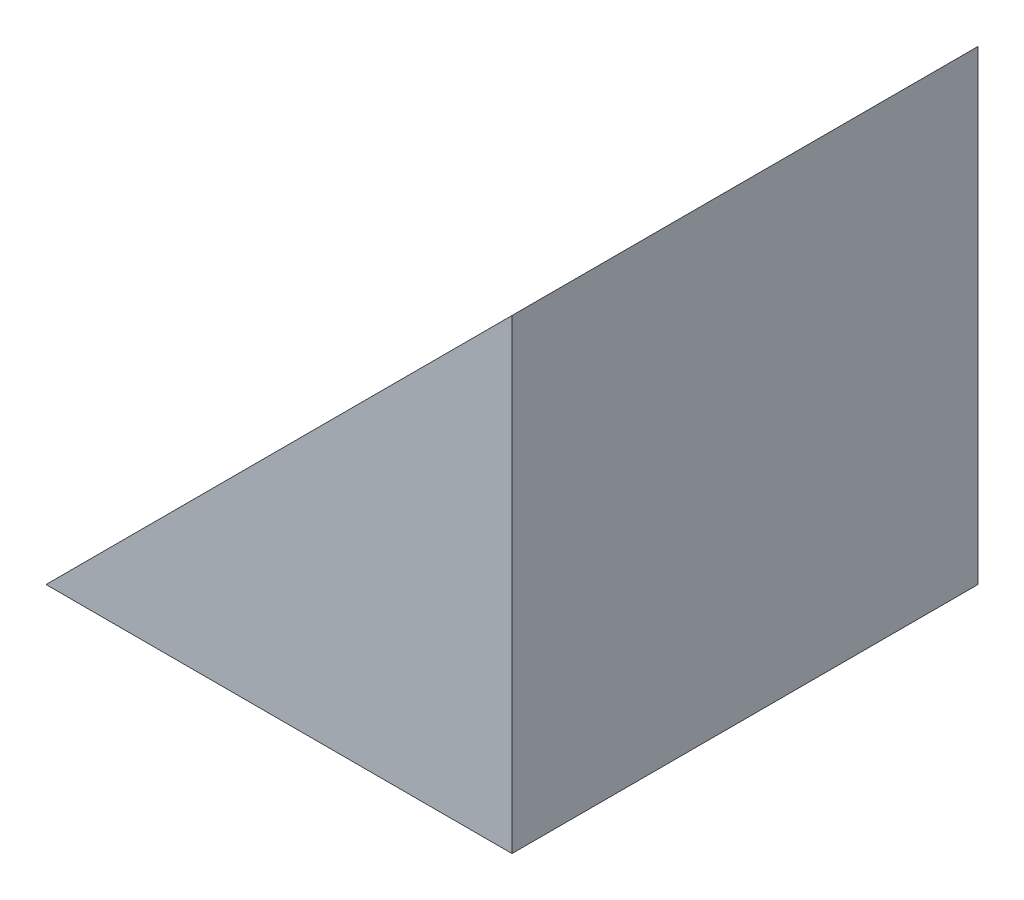
SolidWorks part; units mm, degrees
material "Glass"
ref_plane "Front Plane" through (0, 0, 0) normal (0, 0, 1) x (1, 0, 0)
ref_plane "Top Plane" through (0, 0, 0) normal (0, 1, 0) x (1, 0, 0)
ref_plane "Right Plane" through (0, 0, 0) normal (1, 0, 0) x (0, 0, -1)
sketch "Sketch1" plane through (0, 0, 0) normal (0, 0, 1) x (1, 0, 0)
  line L0 (1, 1) -> (-1, -1)
  line L3 (-1, -1) -> (1, -1)
  line L4 (1, 1) -> (1, -1)
  line L6 (-1, -1) -> (1, 1) construction
  point P0 (0, 0)
  dimension "D2" = 2
extrude "Boss-Extrude1" add sketch "Sketch1" along normal blind 2
